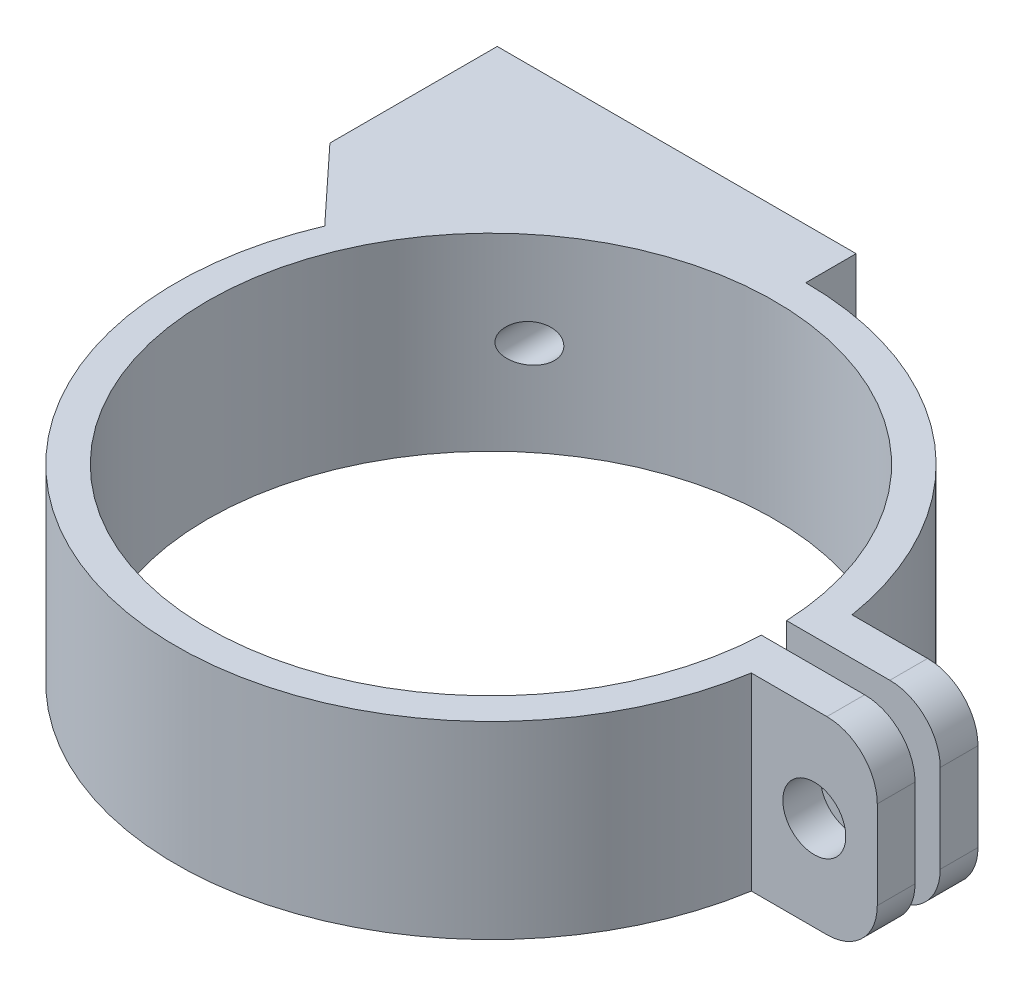
SolidWorks part; units mm, degrees
ref_plane "Alzado" through (0, 0, 0) normal (0, 0, 1) x (1, 0, 0)
ref_plane "Planta" through (0, 0, 0) normal (0, 1, 0) x (1, 0, 0)
ref_plane "Vista lateral" through (0, 0, 0) normal (1, 0, 0) x (0, 0, -1)
sketch "Croquis1" plane through (0, 0, 0) normal (0, 1, 0) x (1, 0, 0)
  line L0 (0, 25) -> (0, 29)
  line L1 (0, 29) -> (-28.5, 29)
  line L2 (-28.5, 29) -> (-28.5, 15.7123)
  line L3 (-28.5, 15.7123) -> (-22.9989, 9.8006)
  line L4 (-22.5, 0) -> (25, 0) construction
  line L5 (22.4778, 1) -> (34.6779, 1)
  line L6 (34.6779, 1) -> (34.6779, 4)
  line L7 (34.6779, 4) -> (24.6779, 4)
  line L8 (22.4778, -1) -> (34.6779, -1)
  line L9 (34.6779, -1) -> (34.6779, -4)
  line L10 (34.6779, -4) -> (24.6779, -4)
  arc A0 (22.4778, 1) -> (22.4778, -1) centre (0, 0) ccw
  arc A1 (-22.9989, 9.8006) -> (24.6779, -4) centre (0, 0) ccw
  arc A2 (24.6779, 4) -> (0, 25) centre (0, 0) ccw
  dimension "D1" = 45
  dimension "D2" = 50
  dimension "D3" = 4
  dimension "D4" = 28.5
  dimension "D5" = 5.9117
  dimension "D6" = 5.5011
  dimension "D7" = 1
  dimension "D8" = 1
  dimension "D9" = 10
  dimension "D10" = 10
  dimension "D11" = 3
  dimension "D12" = 3
extrude "Saliente-Extruir1" add sketch "Croquis1" along normal blind 15
sketch "Croquis2" plane through (0, 0, -29) normal (0, 0, -1) x (-1, 0, 0)
  line L0 (28.5, 15) -> (0, 0) construction
  circle A0 centre (14.25, 7.5) radius 1.5
  dimension "D1" = 3
extrude "Cortar-Extruir1" cut sketch "Croquis2" against normal blind 17
sketch "Croquis3" plane through (0, 0, -4) normal (0, 0, -1) x (-1, 0, 0)
  line L0 (-24.6779, 15) -> (-34.6779, 0) construction
  circle A0 centre (-29.6779, 7.5) radius 2.5
  dimension "D1" = 5
extrude "Cortar-Extruir2" cut sketch "Croquis3" against normal blind 17
fillet "Redondeo1" radius 4 4 edges at (34.6779, 0, 2.5) (34.6779, 0, -2.5) (34.6779, 15, 2.5) (34.6779, 15, -2.5)
